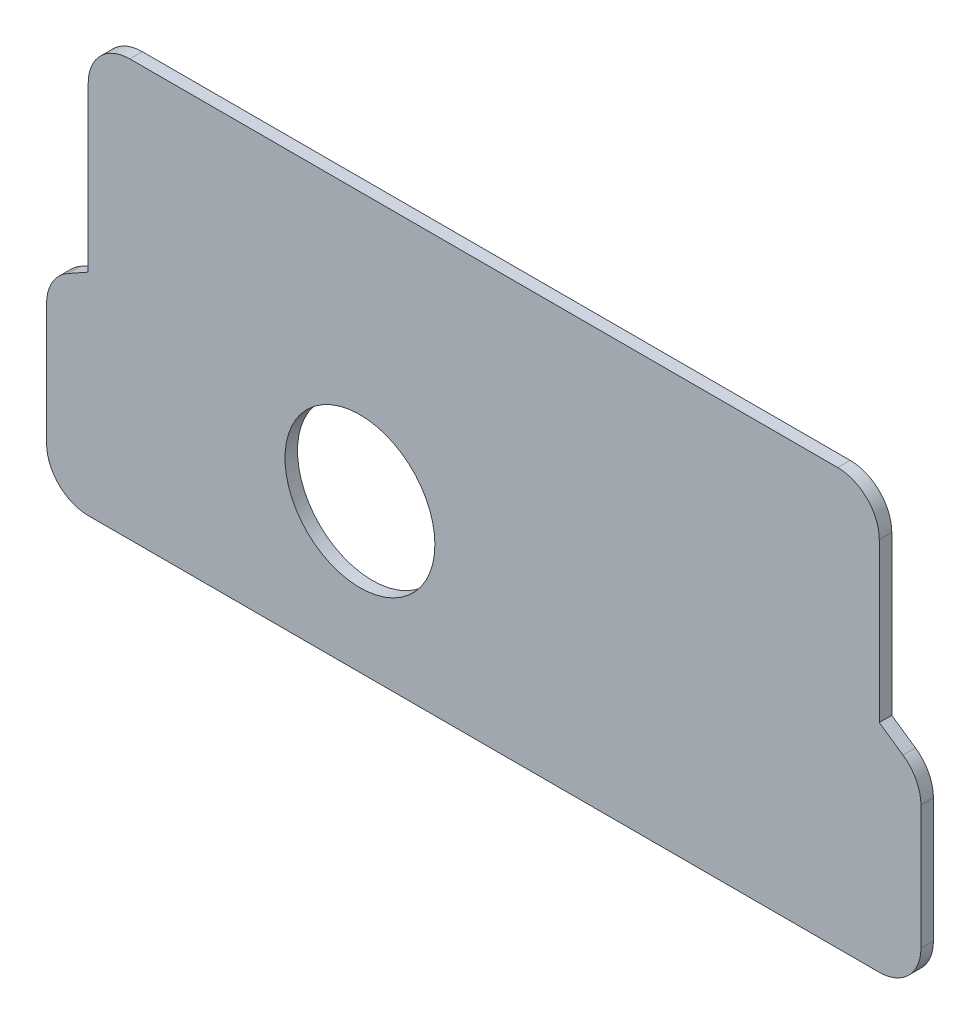
SolidWorks part; units mm, degrees
material "有机玻璃 (TM) GS 丙烯酸铸钣"
ref_plane "前视基准面" through (0, 0, 0) normal (0, 0, 1) x (1, 0, 0)
ref_plane "上视基准面" through (0, 0, 0) normal (0, 1, 0) x (1, 0, 0)
ref_plane "右视基准面" through (0, 0, 0) normal (1, 0, 0) x (0, 0, -1)
other "Configuration Table"
sketch "草图1" plane through (0, 0, 0) normal (0, 0, 1) x (1, 0, 0)
  line L0 (0, 10) -> (0, 39.1866)
  line L1 (5.1248, 47.9177) -> (10, 50.6399)
  line L2 (10, 50.6399) -> (10, 90)
  line L3 (20, 100) -> (190, 100)
  line L4 (200, 90) -> (200, 51.9634)
  line L5 (200, 51.9634) -> (205.6833, 48.0378)
  line L6 (210, 39.8098) -> (210, 10)
  line L7 (200, 0) -> (10, 0)
  line L9 (16.6077, 94.9776) -> (119.8077, 94.9776) construction
  line L10 (16.6077, 94.9776) -> (16.6077, 4.2776) construction
  line L11 (16.6077, 4.2776) -> (119.8077, 4.2776) construction
  line L12 (119.8077, 94.9776) -> (119.8077, 4.2776) construction
  line L13 (126.7178, 83.3205) -> (183.2178, 83.3205) construction
  line L14 (126.7178, 83.3205) -> (126.7178, 11.8205) construction
  line L15 (126.7178, 11.8205) -> (183.2178, 11.8205) construction
  line L16 (183.2178, 83.3205) -> (183.2178, 11.8205) construction
  arc A0 (210, 10) -> (200, 0) centre (200, 10) cw
  arc A1 (0, 10) -> (10, 0) centre (10, 10) ccw
  arc A2 (205.6833, 48.0378) -> (210, 39.8098) centre (200, 39.8098) cw
  arc A3 (0, 39.1866) -> (5.1248, 47.9177) centre (10, 39.1866) cw
  arc A4 (190, 100) -> (200, 90) centre (190, 90) cw
  arc A5 (10, 90) -> (20, 100) centre (20, 90) cw
  circle A6 centre (75.2646, 35.6225) radius 18
  circle A7 centre (75.2646, 35.6225) radius 18 construction
  point P13 (0, 0)
  dimension "D1" = 10
  dimension "D10" = 36
  dimension "D2" = 190
  dimension "D3" = 100
  dimension "D4" = 103.2
  dimension "D5" = 90.7
  dimension "D6" = 71.5
  dimension "D7" = 56.5
  dimension "D8" = 10
  dimension "D9" = 10
extrude "凸台-拉伸1" add sketch "草图1" along normal blind 3
